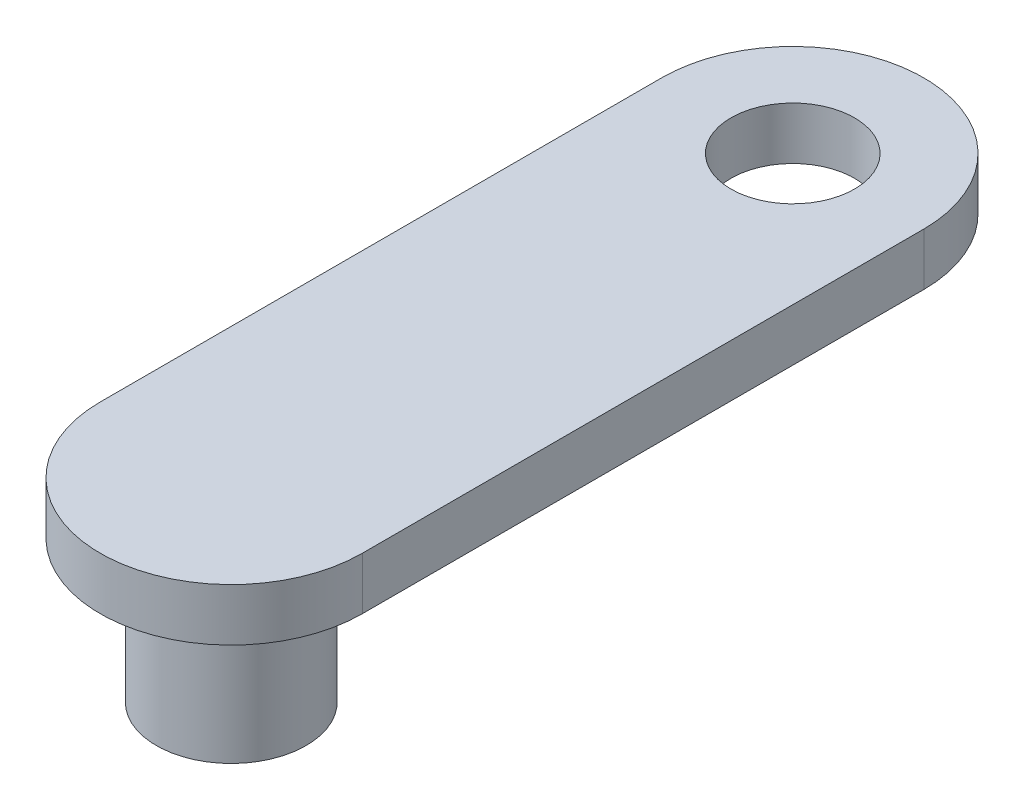
SolidWorks part; units mm, degrees
ref_plane "前视基准面" through (0, 0, 0) normal (0, 0, 1) x (1, 0, 0)
ref_plane "上视基准面" through (0, 0, 0) normal (0, 1, 0) x (1, 0, 0)
ref_plane "右视基准面" through (0, 0, 0) normal (1, 0, 0) x (0, 0, -1)
sketch "草图1" plane through (0, 0, 0) normal (0, 1, 0) x (1, 0, 0)
  circle A0 centre (0, 0) radius 2
  dimension "D1" = 4
extrude "凸台-拉伸1" add sketch "草图1" along normal blind 3.8
sketch "草图2" plane through (0, 3.8, 0) normal (0, 1, 0) x (1, 0, 0)
  line L5 (0, 0) -> (0, 15) construction
  line L6 (-3.5, 0) -> (-3.5, 15)
  line L7 (3.5, 0) -> (3.5, 15)
  circle A2 centre (0, 15) radius 1.65
  arc A3 (-3.5, 0) -> (3.5, 0) centre (0, 0) ccw
  arc A4 (3.5, 15) -> (-3.5, 15) centre (0, 15) ccw
  point P3 (0, 7.5)
  dimension "D1" = 3.3
  dimension "D3" = 3.5
  dimension "D2" = 15
extrude "凸台-拉伸2" add sketch "草图2" along normal blind 1.4
